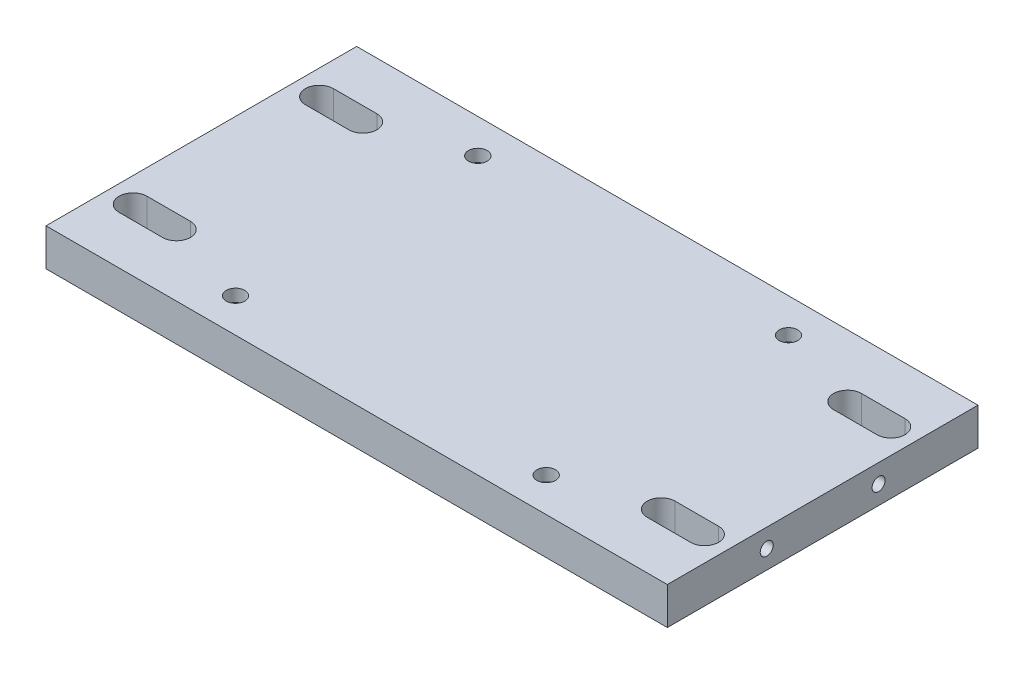
SolidWorks part; units mm, degrees
ref_plane "Front" through (0, 0, 0) normal (0, 0, 1) x (1, 0, 0)
ref_plane "Top" through (0, 0, 0) normal (0, 1, 0) x (1, 0, 0)
ref_plane "Right" through (0, 0, 0) normal (1, 0, 0) x (0, 0, -1)
sketch "Sketch1" plane through (0, 0, 0) normal (0, 1, 0) x (1, 0, 0)
  line L0 (14.9568, 0) -> (-211.527, 0) construction
  line L1 (-200, -50) -> (0, -50)
  line L2 (-200, -50) -> (-200, 50)
  line L3 (-200, 50) -> (0, 50)
  line L4 (0, -50) -> (0, 50)
  dimension "D1" = 200
  dimension "D2" = 100
extrude "Boss-Extrude1" add sketch "Sketch1" along normal blind 12
sketch "Sketch2" plane through (0, 12, 0) normal (0, 1, 0) x (1, 0, 0)
  line L0 (-192, -30) -> (-178, -30) construction
  line L1 (-192, -25.5) -> (-178, -25.5)
  line L2 (-192, -34.5) -> (-178, -34.5)
  line L3 (-192, 30) -> (-178, 30) construction
  line L4 (-192, 34.5) -> (-178, 34.5)
  line L5 (-192, 25.5) -> (-178, 25.5)
  line L6 (-22, 30) -> (-8, 30) construction
  line L7 (-22, 34.5) -> (-8, 34.5)
  line L8 (-22, 25.5) -> (-8, 25.5)
  line L9 (-22, -30) -> (-8, -30) construction
  line L10 (-22, -25.5) -> (-8, -25.5)
  line L11 (-22, -34.5) -> (-8, -34.5)
  line L12 (8.604, 0) -> (-210.0755, 0) construction
  line L14 (0, -50) -> (0, 50) construction
  arc A0 (-192, -25.5) -> (-192, -34.5) centre (-192, -30) ccw
  arc A1 (-178, -34.5) -> (-178, -25.5) centre (-178, -30) ccw
  arc A2 (-192, 34.5) -> (-192, 25.5) centre (-192, 30) ccw
  arc A3 (-178, 25.5) -> (-178, 34.5) centre (-178, 30) ccw
  arc A4 (-22, 34.5) -> (-22, 25.5) centre (-22, 30) ccw
  arc A5 (-8, 25.5) -> (-8, 34.5) centre (-8, 30) ccw
  arc A6 (-22, -25.5) -> (-22, -34.5) centre (-22, -30) ccw
  arc A7 (-8, -34.5) -> (-8, -25.5) centre (-8, -30) ccw
  point P2 (-185, -30)
  point P7 (-185, 30)
  point P14 (-15, 30)
  point P21 (-15, -30)
  dimension "D1" = 60
  dimension "D2" = 9
  dimension "D3" = 170
  dimension "D4" = 14
  dimension "D5" = 15
extrude "Cut-Extrude1" cut sketch "Sketch2" against normal through all
hole_wizard "CBORE for M5 Socket Head Cap Screw1" positions "Sketch4" profile "Sketch3" counterbore size "M5" standard "JIS" end condition through all
sketch "Sketch4" plane through (0, 0, 0) normal (0, -1, 0) x (1, 0, 0)
  line L3 (0, 50) -> (0, -50) construction
  line L4 (14.7778, 0) -> (-207.8253, 0) construction
  point P0 (-150, 39)
  point P1 (-50, 39)
  point P3 (-150, -39)
  point P5 (-50, -39)
  dimension "D1" = 100
  dimension "D2" = 50
  dimension "D3" = 78
sketch "Sketch3" plane through (-150, 0, 39) normal (1, 0, 0) x (0, 0, -1)
  line L0 (0, 0) -> (0, 12)
  line L1 (0, 12) -> (3, 12)
  line L3 (3, 12) -> (3, 8)
  line L4 (3, 8) -> (5.5, 8)
  line L5 (5.5, 8) -> (5.5, 0)
  line L7 (5.5, 0) -> (0, 0)
  line L11 (0, -6.35) -> (0, 107.95) construction
  dimension "Thru Hole Dia." = 6
  dimension "Thru Hole Depth" = 12
  dimension "C'Bore Dia." = 11
  dimension "C'Bore Depth" = 8
hole_wizard "M5x0.8 Tapped Hole1" positions "Sketch6" profile "Sketch5" tap size "M5x0.8" standard "JIS"
sketch "Sketch6" plane through (0, 0, 0) normal (1, 0, 0) x (0, 0, -1)
  line L0 (0, -2.3537) -> (0, 18.3403) construction
  line L2 (-50, 0) -> (50, 0) construction
  point P0 (18, 6)
  point P1 (-18, 6)
  dimension "D1" = 36
  dimension "D2" = 6
sketch "Sketch5" plane through (0, 6, -18) normal (0, 1, 0) x (0, 0, -1)
  line L0 (0, 0) -> (0, 15.2618)
  line L1 (0, 15.2618) -> (2.1, 14)
  line L2 (2.1, 14) -> (2.1, 0)
  line L5 (2.1, 0) -> (0, 0)
  line L10 (0, 15.2618) -> (-2.1, 14) construction
  line L11 (0, -6.35) -> (0, 107.95) construction
  dimension "Tap Drill Dia." = 4.2
  dimension "Tap Drill Depth" = 14
  dimension "Drill Angle" = 118
cosmetic thread "Hole Thread1" parameters "D1"=10, "D2"=5
cosmetic thread "Hole Thread2" parameters "D1"=10, "D2"=5
